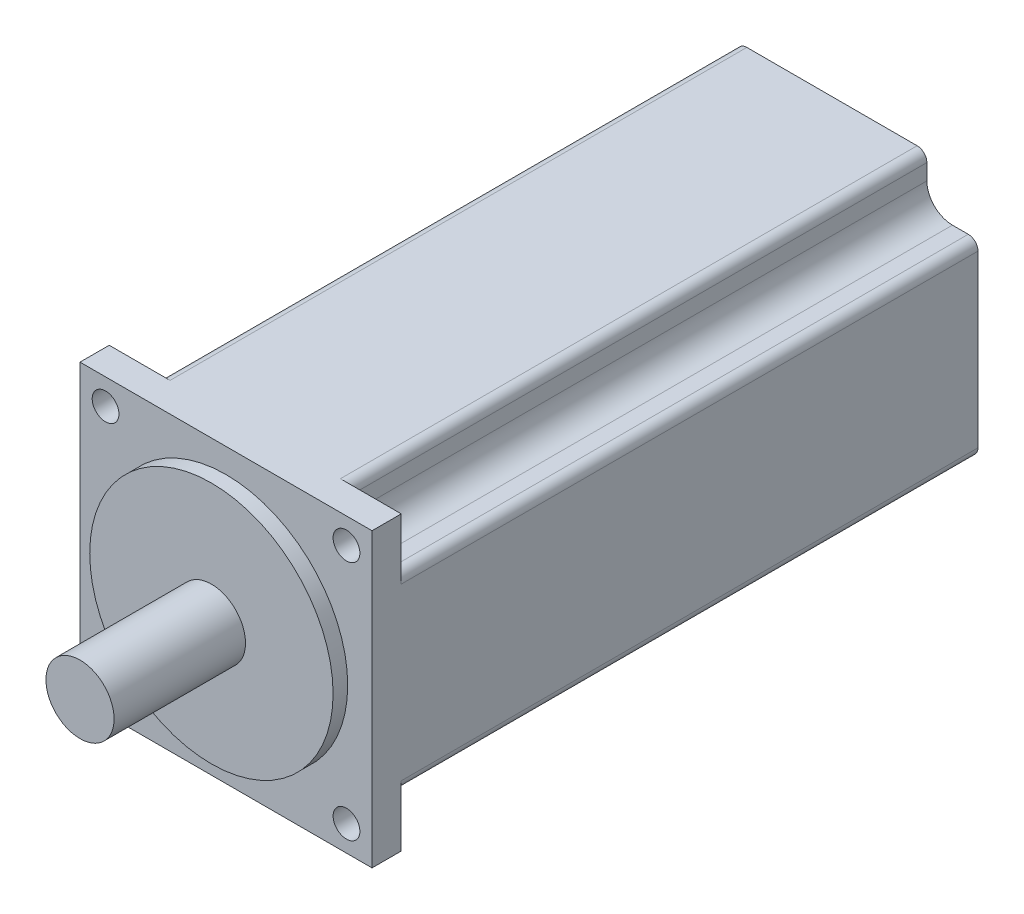
SolidWorks part; units mm, degrees
ref_plane "前视基准面" through (0, 0, 0) normal (0, 0, 1) x (1, 0, 0)
ref_plane "上视基准面" through (0, 0, 0) normal (0, 1, 0) x (1, 0, 0)
ref_plane "右视基准面" through (0, 0, 0) normal (1, 0, 0) x (0, 0, -1)
sketch "草图1" plane through (0, 0, 0) normal (0, 0, 1) x (1, 0, 0)
  line L1 (0, 0) -> (60, 0)
  line L2 (0, 0) -> (0, -60)
  line L3 (0, -60) -> (60, -60)
  line L4 (60, 0) -> (60, -60)
  dimension "D1" = 60
  dimension "D2" = 60
extrude "拉伸1" add sketch "草图1" along normal blind 124.5
sketch "草图2" plane through (0, 0, 124.5) normal (0, 0, 1) x (1, 0, 0)
  circle A0 centre (30, -30) radius 25
extrude "拉伸2" add sketch "草图2" along normal blind 3
sketch "草图3" plane through (0, 0, 127.5) normal (0, 0, 1) x (1, 0, 0)
  circle A0 centre (30, -30) radius 7
extrude "拉伸3" add sketch "草图3" along normal blind 27
sketch "草图4" plane through (0, 0, 124.5) normal (0, 0, 1) x (1, 0, 0)
  circle A1 centre (54.7487, -5.2513) radius 2.75
  circle A2 centre (54.7487, -54.7487) radius 2.75
  circle A3 centre (5.2513, -54.7487) radius 2.75
  circle A4 centre (5.2513, -5.2513) radius 2.75
extrude "切除-拉伸1" cut sketch "草图4" against normal through all
sketch "草图5" plane through (0, 0, 0) normal (0, 0, -1) x (-1, 0, 0)
  line L0 (-10.5025, -5.2513) -> (-10.5025, 0)
  line L1 (-60, 0) -> (0, 0) construction
  line L2 (-5.2513, -10.5025) -> (0, -10.5025)
  line L3 (0, 0) -> (0, -60) construction
  line L4 (0, -10.5025) -> (0, 0)
  line L5 (0, 0) -> (-10.5025, 0)
  line L6 (-49.4975, -54.7487) -> (-49.4975, -60)
  line L8 (-60, 0) -> (-49.4975, 0)
  line L9 (-60, -10.5025) -> (-60, 0)
  line L10 (-54.7487, -10.5025) -> (-60, -10.5025)
  line L11 (-49.4975, -5.2513) -> (-49.4975, 0)
  line L12 (-54.7487, -49.4975) -> (-60, -49.4975)
  line L13 (-60, -49.4975) -> (-60, -60)
  line L14 (-60, -60) -> (-49.4975, -60)
  line L15 (0, -60) -> (-10.5025, -60)
  line L16 (0, -49.4975) -> (0, -60)
  line L17 (-5.2513, -49.4975) -> (0, -49.4975)
  line L18 (-10.5025, -54.7487) -> (-10.5025, -60)
  arc A0 (-10.5025, -5.2513) -> (-5.2513, -10.5025) centre (-5.2513, -5.2513) ccw
  arc A1 (-49.4975, -5.2513) -> (-54.7487, -10.5025) centre (-54.7487, -5.2513) cw
  arc A2 (-49.4975, -54.7487) -> (-54.7487, -49.4975) centre (-54.7487, -54.7487) ccw
  arc A3 (-10.5025, -54.7487) -> (-5.2513, -49.4975) centre (-5.2513, -54.7487) cw
extrude "切除-拉伸2" cut sketch "草图5" against normal blind 118.5
fillet "圆角1" radius 2 8 edges at (60, -10.5025, 59.25) (49.4975, 0, 59.25) (60, -49.4975, 59.25) (49.4975, -60, 59.25) (10.5025, 0, 59.25) (0, -10.5025, 59.25) (10.5025, -60, 59.25) (0, -49.4975, 59.25)
